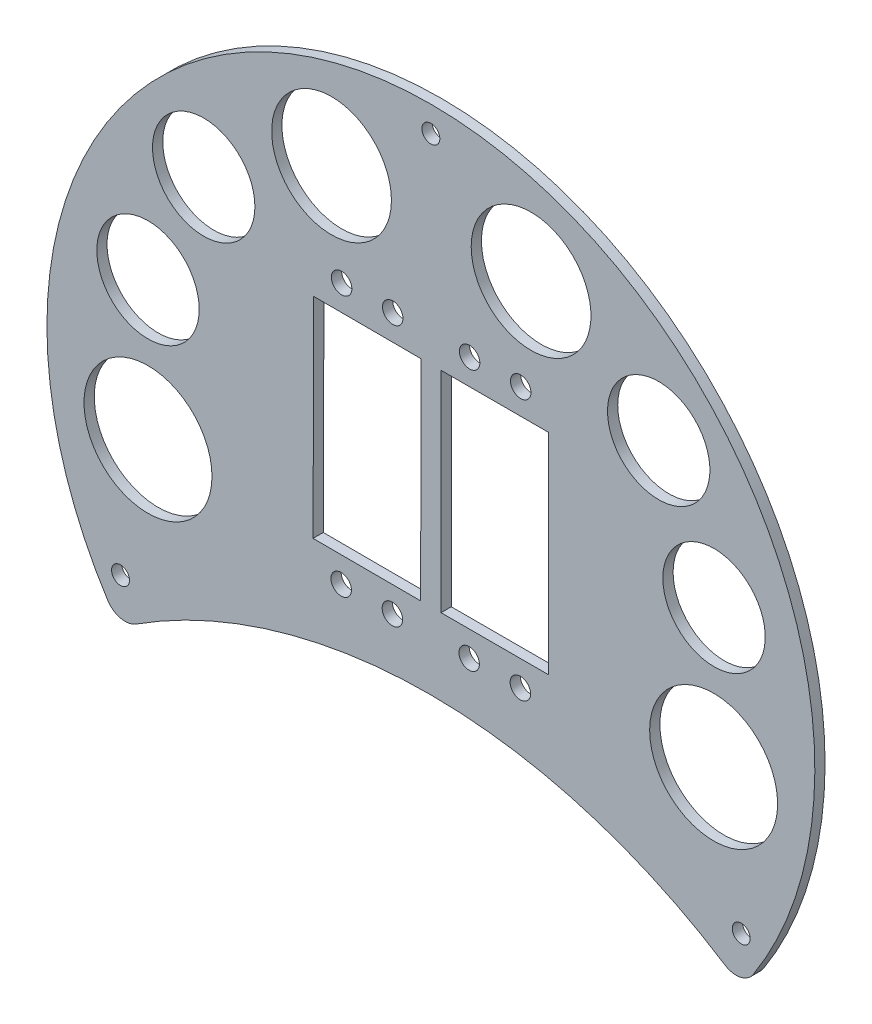
SolidWorks part; units mm, degrees
ref_plane "Plan de face" through (0, 0, 0) normal (0, 0, 1) x (1, 0, 0)
ref_plane "Plan de dessus" through (0, 0, 0) normal (0, 1, 0) x (1, 0, 0)
ref_plane "Plan de droite" through (0, 0, 0) normal (1, 0, 0) x (0, 0, -1)
sketch "Esquisse3" plane through (0, 0, 0) normal (0, 0, 1) x (1, 0, 0)
  arc A0 (60.6768, -44.0831) -> (-60.8091, -43.9004) centre (0, 0) ccw
  arc A1 (-60.8091, -43.9004) -> (60.6768, -44.0831) centre (-0.1975, -131.3197) cw
  dimension "D1" = 150
extrude "Epaisseur plaque" add sketch "Esquisse3" along normal blind 2
sketch "Esquisse5" plane through (0, 0, 2) normal (0, 0, 1) x (1, 0, 0)
  line L0 (0, 78.5845) -> (0, -78.7837) construction
  line L1 (-80.0785, 0) -> (86.8513, 0) construction
  circle A0 centre (0, 70) radius 1.75
  circle A1 centre (0, 0) radius 75 construction
  circle A2 centre (0, 0) radius 75 construction
  circle A3 centre (60.6218, -35) radius 1.75
  circle A4 centre (-60.6218, -35) radius 1.75
  point P10 (0, 75)
  point P20 (0, 0)
  dimension "D1" = 3.5
  dimension "D2" = 5
  dimension "D3" = 3
extrude "Percage fis fixations" cut sketch "Esquisse5" against normal blind 2
fillet "Arrondis extremites" radius 4 2 edges at (-60.8091, -43.9004, 1) (60.6768, -44.0831, 1)
sketch "Esquisse10" plane through (0, 0, 2) normal (0, 0, 1) x (1, 0, 0)
  line L0 (0, 0) -> (0.1128, 74.9999) construction
  arc A0 (62.9773, -40.729) -> (-63.0996, -40.5394) centre (0, 0) ccw construction
  circle A2 centre (-44.3755, 40.4604) radius 10
  circle A3 centre (-55.2591, 17.6479) radius 10
  circle A4 centre (-55.2591, -9.3659) radius 12.5
  circle A5 centre (55.2307, -9.5321) radius 12.5
  circle A6 centre (55.3119, 17.4817) radius 10
  circle A7 centre (44.497, 40.3267) radius 10
  circle A9 centre (-19.4045, 54.8728) radius 11.6978
  circle A10 centre (19.5694, 54.8142) radius 11.6978
  dimension "D1" = 20
  dimension "D2" = 20
  dimension "D3" = 25
extrude "Evidement de matière" cut sketch "Esquisse10" against normal blind 2
sketch "Esquisse11" plane through (0, 0, 2) normal (0, 0, 1) x (1, 0, 0)
  line L0 (0, 0) -> (0.1128, 74.9999) construction
  line L1 (12.4556, -29.5164) -> (12.6112, 73.9321) construction
  line L2 (17.5463, 35.959) -> (17.4774, -15.041) construction
  line L11 (-2.0151, -10.035) -> (-23.015, -9.9718)
  line L12 (1.9849, 30.959) -> (22.9849, 30.959)
  line L13 (1.9849, 30.959) -> (1.9849, -10.041)
  line L14 (1.9849, -10.041) -> (22.9849, -10.041)
  line L15 (22.9849, 30.959) -> (22.9849, -10.041)
  line L16 (-1.8918, 30.9648) -> (-2.0151, -10.035)
  line L17 (-22.8917, 31.028) -> (-23.015, -9.9718)
  line L18 (-1.8918, 30.9648) -> (-22.8917, 31.028)
  line L19 (1.9849, 30.459) -> (22.9849, 30.459) construction
  line L20 (1.9849, -9.541) -> (22.9849, -9.541) construction
  arc A2 (62.9773, -40.729) -> (-63.0996, -40.5394) centre (0, 0) ccw construction
  circle A3 centre (17.5463, 35.959) radius 2
  circle A5 centre (17.4774, -15.041) radius 2
  circle A7 centre (7.4774, -15.0259) radius 2
  circle A8 centre (7.5619, 35.974) radius 2
  circle A9 centre (7.4774, -15.0259) radius 2
  circle A10 centre (17.4774, -15.041) radius 2
  circle A11 centre (17.5463, 35.959) radius 2
  circle A12 centre (7.5619, 35.974) radius 2
  circle A13 centre (-17.5226, -14.9883) radius 2
  circle A14 centre (-7.5226, -15.0034) radius 2
  circle A15 centre (-17.4381, 36.0116) radius 2
  circle A16 centre (-7.4536, 35.9966) radius 2
  point P21 (12.4849, -10.041)
  dimension "D2" = 5.5
  dimension "D4" = 5
  dimension "D5" = 4
  dimension "D6" = 4
  dimension "D3" = 12.5
  dimension "D7" = 21
  dimension "D8" = 0.5
  dimension "D9" = 0.5
  dimension "D10" = 41
  dimension "D11" = 40
  dimension "D12" = 5.515
  dimension "D13" = 5.5
extrude "Emplacements servomoteurs" cut sketch "Esquisse11" against normal blind 10 contours L16 L18 L17 L11 | L15 L12 L13 L14 | A8 | A3 | A16 | A15 | A13 | A5 | A7 | A14
